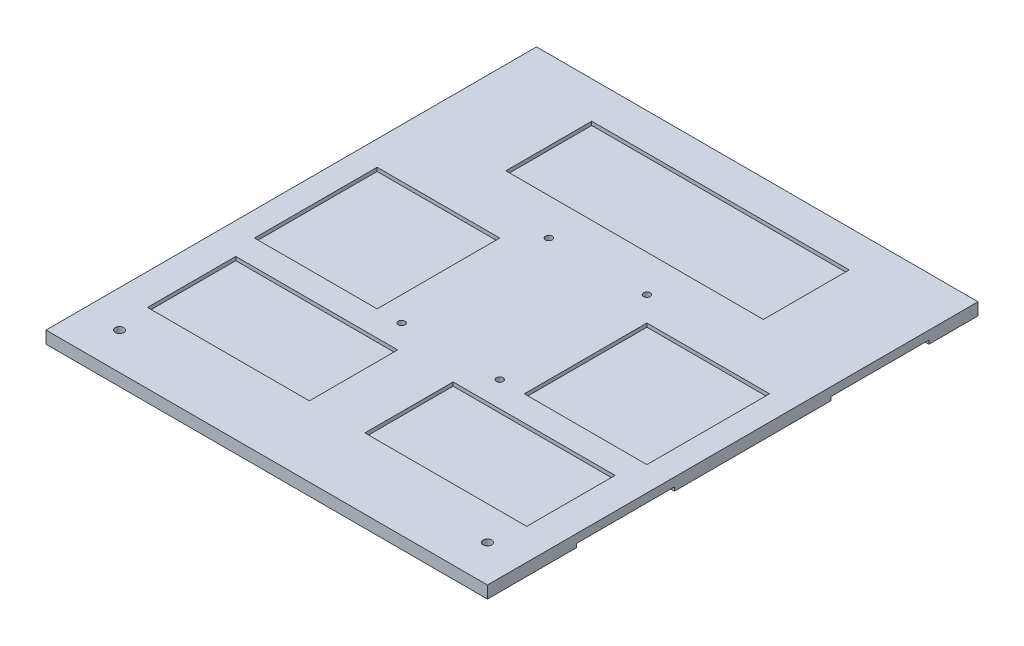
SolidWorks part; units mm, degrees
ref_plane "Front Plane" through (0, 0, 0) normal (0, 0, 1) x (1, 0, 0)
ref_plane "Top Plane" through (0, 0, 0) normal (0, 1, 0) x (1, 0, 0)
ref_plane "Right Plane" through (0, 0, 0) normal (1, 0, 0) x (0, 0, -1)
sketch "Sketch1" plane through (0, 0, 0) normal (0, 1, 0) x (1, 0, 0)
  line L1 (-90, 100) -> (90, 100)
  line L2 (-90, 100) -> (-90, -100)
  line L3 (-90, -100) -> (90, -100)
  line L4 (90, 100) -> (90, -100)
  line L5 (-90, 100) -> (90, -100) construction
  line L6 (-90, -100) -> (90, 100) construction
  point P0 (0, 0)
  dimension "D1" = 200
  dimension "D2" = 180
extrude "Boss-Extrude1" add sketch "Sketch1" along normal blind 12.5
sketch "Sketch2" plane through (0, 12.5, 0) normal (0, 1, 0) x (1, 0, 0)
  line L1 (0, 111.2865) -> (0, -114.9682) construction
  line L2 (-151.6174, 0) -> (135.8867, 0) construction
  line L4 (146.2623, 39.3268) -> (146.9317, 39.6615) construction
  line L5 (-42.5, 27.5) -> (42.5, 27.5)
  line L6 (-42.5, 27.5) -> (-42.5, -27.5)
  line L7 (-42.5, -27.5) -> (42.5, -27.5)
  line L8 (42.5, 27.5) -> (42.5, -27.5)
  line L9 (-42.5, 27.5) -> (42.5, -27.5) construction
  line L10 (-42.5, -27.5) -> (42.5, 27.5) construction
  point P5 (0, 0)
  dimension "D1" = 55
  dimension "D2" = 85
extrude "Cut-Extrude1" cut sketch "Sketch2" against normal blind 1.5
sketch "Sketch3" plane through (0, 12.5, 0) normal (0, 1, 0) x (1, 0, 0)
  line L0 (0, 115.0439) -> (0, 37.64) construction
  line L1 (-52.5, 85) -> (52.5, 85)
  line L2 (-52.5, 85) -> (-52.5, 50)
  line L3 (-52.5, 50) -> (52.5, 50)
  line L4 (52.5, 85) -> (52.5, 50)
  line L5 (-52.5, 85) -> (52.5, 50) construction
  line L6 (-52.5, 50) -> (52.5, 85) construction
  line L7 (90, 100) -> (-90, 100) construction
  point P0 (0, 67.5)
  dimension "D1" = 35
  dimension "D2" = 105
  dimension "D3" = 15
extrude "Cut-Extrude2" cut sketch "Sketch3" against normal blind 1.5
sketch "Sketch4" plane through (0, 0, 0) normal (0, -1, 0) x (1, 0, 0)
  line L4 (90, -100) -> (90, 100)
  line L5 (90, 100) -> (-90, 100)
  line L6 (-90, 100) -> (-90, -100)
  line L7 (-90, -100) -> (90, -100)
  line L8 (90, -100) -> (90, 100)
  line L9 (90, 100) -> (-90, 100)
  line L10 (-90, 100) -> (-90, -100)
  line L11 (-90, -100) -> (90, -100)
  dimension "D1" = 0
extrude "Cut-Extrude3" cut sketch "Sketch4" against normal blind 4.5
sketch "Sketch5" plane through (0, 4.5, 0) normal (0, -1, 0) x (1, 0, 0)
  line L4 (-90, -100) -> (90, -100)
  line L5 (90, -100) -> (90, 100)
  line L6 (90, 100) -> (-90, 100)
  line L7 (-90, 100) -> (-90, -100)
  line L8 (-90, -100) -> (90, -100)
  line L9 (90, -100) -> (90, 100)
  line L10 (90, 100) -> (-90, 100)
  line L11 (-90, 100) -> (-90, -100)
  dimension "D1" = 0
extrude "Cut-Extrude4" cut sketch "Sketch5" against normal blind 3
sketch "Sketch7" plane through (0, 11, 0) normal (0, 1, 0) x (1, 0, 0)
  line L4 (42.5, -27.5) -> (42.5, 27.5)
  line L5 (42.5, 27.5) -> (-42.5, 27.5)
  line L6 (-42.5, 27.5) -> (-42.5, -27.5)
  line L7 (-42.5, -27.5) -> (42.5, -27.5)
  line L8 (42.5, -27.5) -> (42.5, 27.5)
  line L9 (42.5, 27.5) -> (-42.5, 27.5)
  line L10 (-42.5, 27.5) -> (-42.5, -27.5)
  line L11 (-42.5, -27.5) -> (42.5, -27.5)
  dimension "D1" = 0
extrude "Boss-Extrude2" add sketch "Sketch7" along normal blind 1.5
sketch "Sketch8" plane through (0, 12.5, 0) normal (0, 1, 0) x (1, 0, 0)
  line L0 (0, 107.8001) -> (0, -109.4736) construction
  line L1 (-159.2597, 0) -> (140.8514, 0) construction
  line L2 (80, -25) -> (30, -25)
  line L3 (-80, 25) -> (-30, 25)
  line L4 (-80, 25) -> (-80, -25)
  line L5 (-80, -25) -> (-30, -25)
  line L6 (-30, 25) -> (-30, -25)
  line L7 (-80, 25) -> (-30, -25) construction
  line L8 (-80, -25) -> (-30, 25) construction
  line L9 (30, 25) -> (30, -25)
  line L10 (80, 25) -> (30, 25)
  line L11 (80, 25) -> (80, -25)
  point P5 (-55, 0)
  dimension "D1" = 50
  dimension "D2" = 50
  dimension "D3" = 30
extrude "Cut-Extrude5" cut sketch "Sketch8" against normal blind 1.5
sketch "Sketch9" plane through (0, 12.5, 0) normal (0, 1, 0) x (1, 0, 0)
  line L0 (0, 114.2988) -> (0, -120.658) construction
  line L1 (-107.7722, 0) -> (171.0298, 0) construction
  line L2 (-92.5111, -53.3105) -> (148.1355, -53.3105) construction
  line L3 (77.3148, -71.3105) -> (11.3148, -71.3105)
  line L4 (-77.3148, -35.3105) -> (-11.3148, -35.3105)
  line L5 (-77.3148, -35.3105) -> (-77.3148, -71.3105)
  line L6 (-77.3148, -71.3105) -> (-11.3148, -71.3105)
  line L7 (-11.3148, -35.3105) -> (-11.3148, -71.3105)
  line L8 (-77.3148, -35.3105) -> (-11.3148, -71.3105) construction
  line L9 (-77.3148, -71.3105) -> (-11.3148, -35.3105) construction
  line L10 (11.3148, -35.3105) -> (11.3148, -71.3105)
  line L11 (77.3148, -35.3105) -> (11.3148, -35.3105)
  line L12 (77.3148, -35.3105) -> (77.3148, -71.3105)
  point P7 (-44.3148, -53.3105)
  dimension "D1" = 66
  dimension "D2" = 36
extrude "Cut-Extrude6" cut sketch "Sketch9" against normal blind 1.5
sketch "Sketch11" plane through (0, 7.5, 0) normal (0, -1, 0) x (1, 0, 0)
  line L0 (0, 109.4736) -> (0, -110.5892) construction
  line L1 (-133.8785, 0) -> (128.0213, 0) construction
  line L2 (-90, 100) -> (-90, -100) construction
  line L7 (130, 23.7881) -> (50, 63.7881) construction
  line L8 (-130, 63.7881) -> (-50, 63.7881)
  line L9 (-90, 109.4736) -> (-90, -110.5892) construction
  line L10 (-50, -81.2119) -> (-130, -41.2119) construction
  line L15 (-130, -41.2119) -> (-50, -41.2119)
  line L16 (-50, -81.2119) -> (-50, -41.2119)
  line L17 (-130, -81.2119) -> (-50, -81.2119)
  line L18 (-130, -81.2119) -> (-130, -41.2119)
  line L19 (130, -80) -> (130, -40)
  line L20 (130, -80) -> (50, -80)
  line L21 (50, -80) -> (50, -40)
  line L22 (130, -40) -> (50, -40)
  line L23 (-130, 63.7881) -> (-130, 23.7881)
  line L24 (-48.5, 99.4112) -> (48.5, 99.4112)
  line L25 (-48.5, 99.4112) -> (-48.5, 79.4112)
  line L26 (-48.5, 79.4112) -> (48.5, 79.4112)
  line L27 (48.5, 99.4112) -> (48.5, 79.4112)
  line L28 (-48.5, 99.4112) -> (48.5, 79.4112) construction
  line L29 (-48.5, 79.4112) -> (48.5, 99.4112) construction
  line L30 (-130, 23.7881) -> (-50, 23.7881)
  line L31 (-50, 63.7881) -> (-50, 23.7881)
  line L32 (-130, 63.7881) -> (-50, 23.7881) construction
  line L33 (-130, 23.7881) -> (-50, 63.7881) construction
  line L34 (130, 63.7881) -> (50, 23.7881) construction
  line L35 (90, 109.4736) -> (90, -110.5892) construction
  line L36 (50, 63.7881) -> (50, 23.7881)
  line L37 (130, 23.7881) -> (50, 23.7881)
  line L38 (130, 63.7881) -> (130, 23.7881)
  line L39 (130, 63.7881) -> (50, 63.7881)
  line L40 (-130, -81.2119) -> (-50, -41.2119) construction
  point P5 (-90, 50)
  point P6 (-90, 43.7881)
  point P28 (0, 89.4112)
  point P34 (90, 43.7881)
  point P35 (90, 50)
  dimension "D1" = 65
  dimension "D2" = 80
  dimension "D3" = 40
  dimension "D4" = 97
  dimension "D5" = 20
extrude "Cut-Extrude9" cut sketch "Sketch11" against normal blind 1.5
sketch "Sketch15" plane through (0, 7.5, 0) normal (0, -1, 0) x (1, 0, 0)
  line L0 (-20, 25) -> (-20, 100) construction
  line L1 (90, -40) -> (90, 23.7881) construction
  line L2 (90, 100) -> (-90, 100) construction
  line L3 (-20, 25) -> (20, 25) construction
  line L4 (20, 25) -> (20, -35) construction
  line L5 (20, -35) -> (90, -35) construction
  circle A0 centre (-20, 25) radius 1.35
  circle A1 centre (20, 25) radius 1.35
  circle A2 centre (-20, -35) radius 1.35
  circle A3 centre (20, -35) radius 1.35
  dimension "D1" = 2.7
  dimension "D3" = 2.7
  dimension "D5" = 2.7
  dimension "D6" = 2.7
  dimension "D2" = 75
  dimension "D4" = 40
  dimension "D7" = 70
  dimension "D8" = 60
extrude "Cut-Extrude11" cut sketch "Sketch15" against normal through all
sketch "Sketch16" plane through (0, 12.5, 0) normal (0, 1, 0) x (1, 0, 0)
  line L0 (0, -100) -> (0, -75.3545) construction
  line L1 (-90, -100) -> (90, -100) construction
  line L2 (-90, 100) -> (-90, -100) construction
  circle A0 centre (-75, -85) radius 1.75
  circle A1 centre (75, -85) radius 1.75
  dimension "D1" = 3.5
  dimension "D2" = 15
  dimension "D3" = 15
extrude "Cut-Extrude12" cut sketch "Sketch16" against normal up to surface (5 mm away) up to face at (20, 7.5, 23.65)
equation "\"A\"= 200mm"
equation "\"B\"= 180mm"
equation "\"D1@Sketch1\"=\"A\""
equation "\"D2@Sketch1\"=\"B\""
